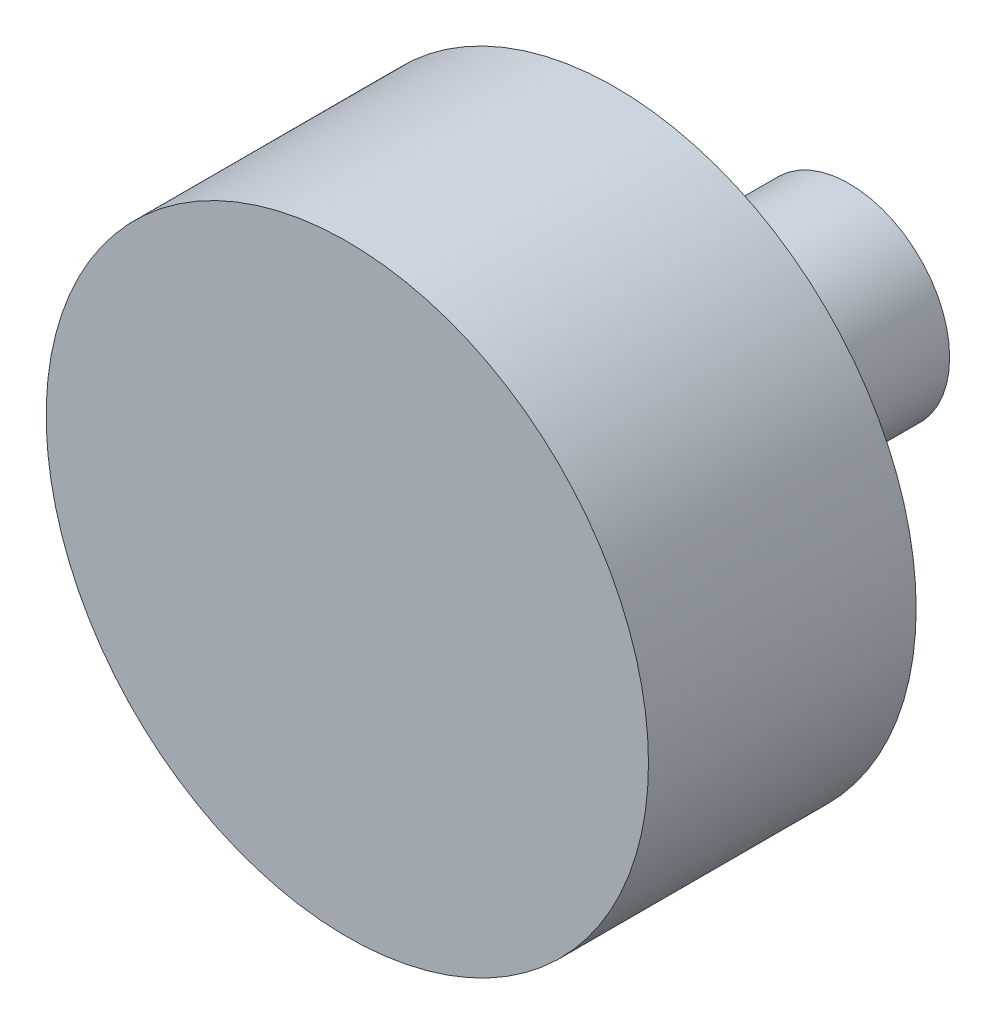
SolidWorks part; units mm, degrees
ref_plane "Plano frontal" through (0, 0, 0) normal (0, 0, 1) x (1, 0, 0)
ref_plane "Plano superior" through (0, 0, 0) normal (0, 1, 0) x (1, 0, 0)
ref_plane "Plano direito" through (0, 0, 0) normal (1, 0, 0) x (0, 0, -1)
sketch "Esboço1" plane through (0, 0, 0) normal (0, 0, 1) x (1, 0, 0)
  circle A0 centre (0, 0) radius 9
extrude "Ressalto-extrusão1" add sketch "Esboço1" along normal blind 5 and the other way blind 3
ref_plane "Plano1" through (0, 0, 0) normal (0, 0, 1) x (1, 0, 0)
sketch "Esboço2" plane through (0, 0, 0) normal (0, 0, 1) x (1, 0, 0)
  circle A0 centre (0, 0) radius 3
extrude "Ressalto-extrusão2" add sketch "Esboço2" against normal blind 10
sketch "Esboço3" plane through (0, 0, 0) normal (0, 0, 1) x (1, 0, 0)
  circle A0 centre (0, 0) radius 6
  circle A2 centre (0, 0) radius 3
extrude "Corte-extrusão1" cut sketch "Esboço3" against normal blind 10
